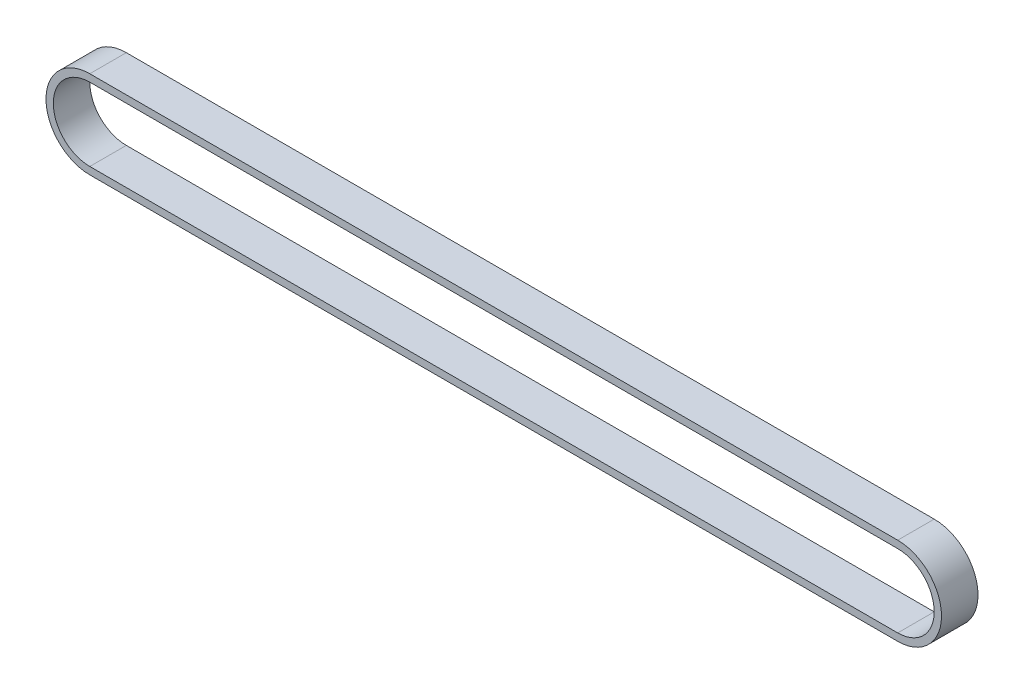
SolidWorks part; units mm, degrees
ref_plane "前视基准面" through (0, 0, 0) normal (0, 0, 1) x (1, 0, 0)
ref_plane "上视基准面" through (0, 0, 0) normal (0, 1, 0) x (1, 0, 0)
ref_plane "右视基准面" through (0, 0, 0) normal (1, 0, 0) x (0, 0, -1)
sketch "草图1" plane through (0, 0, 0) normal (0, 0, 1) x (1, 0, 0)
  line L0 (0, 0) -> (-332, 0) construction
  line L1 (0, -15) -> (-332, -15)
  line L2 (0, 15) -> (-332, 15)
  line L3 (0, -18) -> (-332, -18)
  line L4 (0, 18) -> (-332, 18)
  arc A0 (0, -15) -> (0, 15) centre (0, 0) ccw
  arc A1 (-332, 15) -> (-332, -15) centre (-332, 0) ccw
  arc A2 (-332, 18) -> (-332, -18) centre (-332, 0) ccw
  arc A3 (0, -18) -> (0, 18) centre (0, 0) ccw
  point P3 (-166, 0)
  dimension "D1" = 15
  dimension "D2" = 332
  dimension "D3" = 3
extrude "凸台-拉伸1" add sketch "草图1" along normal blind 15
